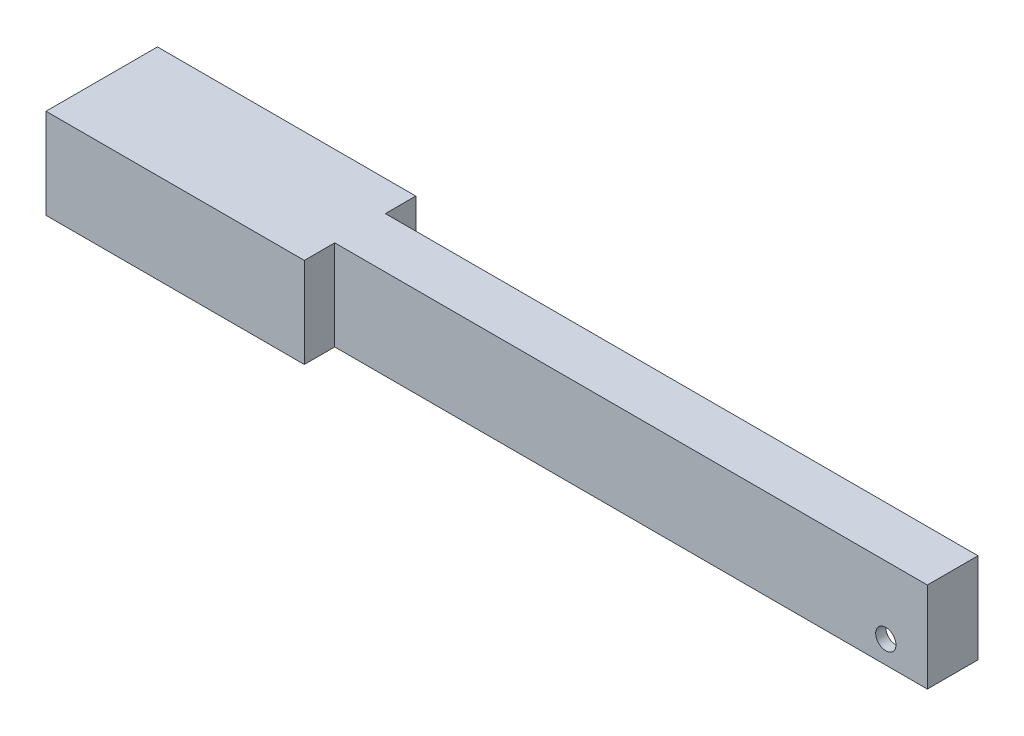
SolidWorks part; units mm, degrees
ref_plane "Front Plane" through (0, 0, 0) normal (0, 0, 1) x (1, 0, 0)
ref_plane "Top Plane" through (0, 0, 0) normal (0, 1, 0) x (1, 0, 0)
ref_plane "Right Plane" through (0, 0, 0) normal (1, 0, 0) x (0, 0, -1)
sketch "Sketch1" plane through (0, 0, 0) normal (0, 1, 0) x (1, 0, 0)
  line L1 (-84, -11) -> (84, -11)
  line L2 (-84, -11) -> (-84, 11)
  line L3 (-84, 11) -> (84, 11)
  line L4 (84, -11) -> (84, 11)
  line L5 (-84, -11) -> (84, 11) construction
  line L6 (-84, 11) -> (84, -11) construction
  point P0 (0, 0)
  dimension "D1" = 22
  dimension "D2" = 168
extrude "Boss-Extrude1" add sketch "Sketch1" against normal blind 17.8 contours L2 L3 L4 L1
sketch "Sketch8" plane through (0, 0, 11) normal (0, 0, 1) x (1, 0, 0)
  line L0 (84, 0) -> (51.2, -17.8) construction
  line L1 (-84, -17.8) -> (84, -17.8) construction
  line L3 (67.6, -8.9) -> (84, -8.9) construction
  line L4 (84, -17.8) -> (84, 0) construction
  line L5 (75.8, -8.9) -> (75.8, -17.8) construction
  circle A0 centre (75.8, -13.35) radius 2
  dimension "D1" = 4
extrude "Cut-Extrude4" cut sketch "Sketch8" against normal up to surface (22 mm away) up to face at (0, -8.9, -11)
sketch "Sketch5" plane through (0, 0, 0) normal (0, 1, 0) x (1, 0, 0)
  line L0 (-84, 11) -> (84, 11) construction
  line L1 (-33, 11) -> (84, 11)
  line L2 (-33, 11) -> (-33, 5)
  line L3 (-33, 5) -> (84, 5)
  line L4 (84, 11) -> (84, 5)
  line L5 (-33, 11) -> (84, 5) construction
  line L6 (-33, 5) -> (84, 11) construction
  line L7 (84, -11) -> (84, 11) construction
  line L8 (-84, -11) -> (84, -11) construction
  line L9 (-33, -11) -> (84, -11)
  line L10 (-33, -11) -> (-33, -5)
  line L11 (-33, -5) -> (84, -5)
  line L12 (84, -11) -> (84, -5)
  line L13 (-33, -11) -> (84, -5) construction
  line L14 (-33, -5) -> (84, -11) construction
  point P0 (25.5, 8)
  point P9 (25.5, -8)
  dimension "D1" = 117
  dimension "D2" = 6
extrude "Cut-Extrude2" cut sketch "Sketch5" against normal up to surface (17.8 mm away) up to face at (0, -17.8, 0)
sketch "Sketch6" plane through (0, -17.8, 0) normal (0, -1, 0) x (1, 0, 0)
  line L0 (-82, 9) -> (-82, -9)
  line L1 (-82, -9) -> (-35, -9)
  line L2 (-35, -9) -> (-35, -3)
  line L3 (-35, -3) -> (82, -3)
  line L5 (-35, 9) -> (-82, 9)
  line L6 (-84, 11) -> (-33, 11) construction
  line L7 (-84, 11) -> (-84, -11) construction
  line L8 (-84, -11) -> (-33, -11) construction
  line L9 (-33, -5) -> (-33, -11) construction
  line L10 (84, -5) -> (-33, -5) construction
  line L12 (-35, 9) -> (-35, 3)
  line L13 (-35, 3) -> (82, 3)
  line L14 (82, 3) -> (82, -3)
  line L15 (84, 5) -> (84, -5) construction
  line L16 (-33, 5) -> (84, 5) construction
  dimension "D1" = 2
  dimension "D2" = 2
  dimension "D3" = 2
  dimension "D4" = 2
  dimension "D5" = 2
  dimension "D6" = 2
  dimension "D7" = 2
extrude "Cut-Extrude3" cut sketch "Sketch6" against normal offset from surface (15.8 mm away) 2 up to face at (-16.5, 0, 0)
sketch "Sketch7" plane through (0, 0, -9) normal (0, 0, 1) x (1, 0, 0)
  line L0 (-82, -12.3) -> (-35, -12.3)
  line L1 (-82, -12.3) -> (-82, -14.3)
  line L2 (-35, -12.3) -> (-35, -14.3)
  line L3 (-82, -14.3) -> (-35, -14.3)
  line L4 (-82, -2) -> (-82, -17.8) construction
  line L5 (-35, -2) -> (-35, -17.8) construction
  line L7 (-82, -17.8) -> (-35, -17.8) construction
  dimension "D1" = 3.5
  dimension "D2" = 2
extrude "Boss-Extrude3" add sketch "Sketch7" along normal up to surface (18 mm away) up to face at (-58.5, -9.9, 9)
